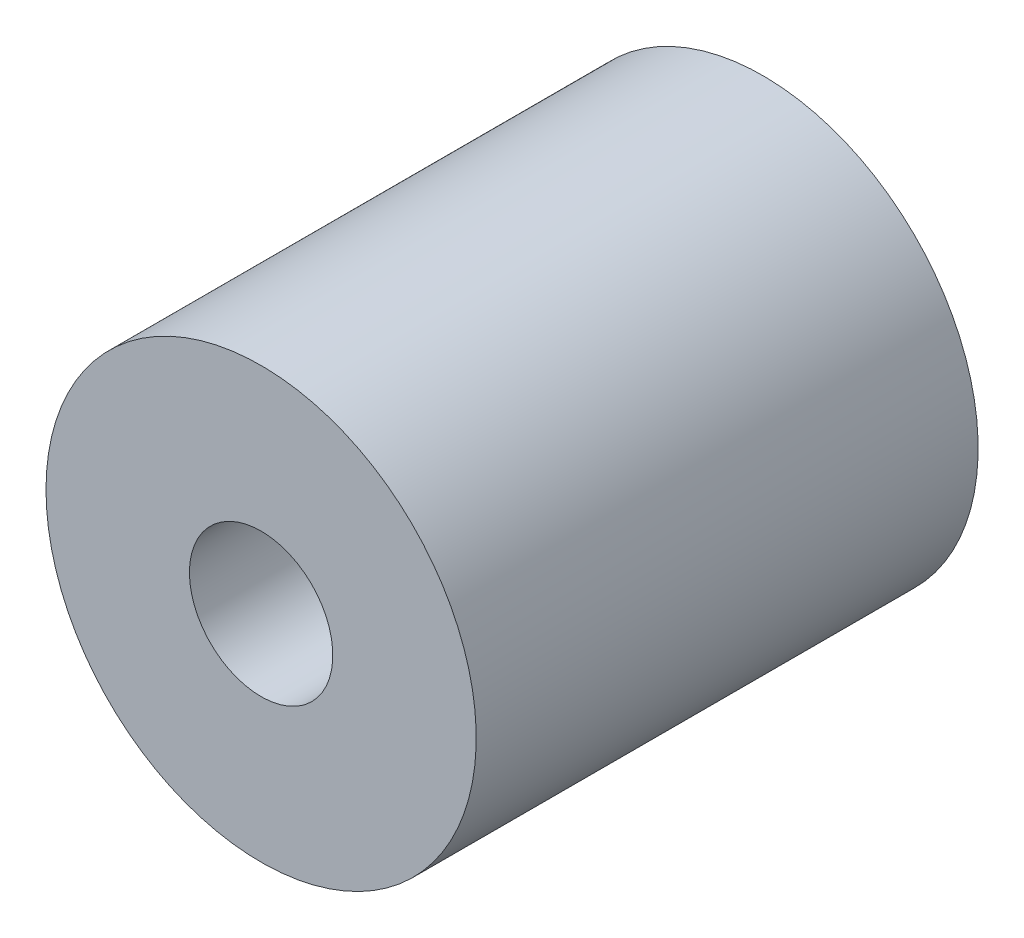
SolidWorks part; units mm, degrees
ref_plane "Front Plane" through (0, 0, 0) normal (0, 0, 1) x (1, 0, 0)
ref_plane "Top Plane" through (0, 0, 0) normal (0, 1, 0) x (1, 0, 0)
ref_plane "Right Plane" through (0, 0, 0) normal (1, 0, 0) x (0, 0, -1)
sketch "AnnulusProfile" plane through (0, 0, 0) normal (0, 1, 0) x (1, 0, 0)
  line L1 (2, 0) -> (6, 0)
  line L2 (2, 0) -> (2, -14)
  line L3 (2, -14) -> (6, -14)
  line L4 (6, 0) -> (6, -14)
  line L5 (0, 0) -> (0, -20) construction
  dimension "inner_radius_mm" = 2
  dimension "outer_radius_mm" = 6
  dimension "height_mm" = 14
revolve "Revolution" add sketch "AnnulusProfile" angle 360 about L5
